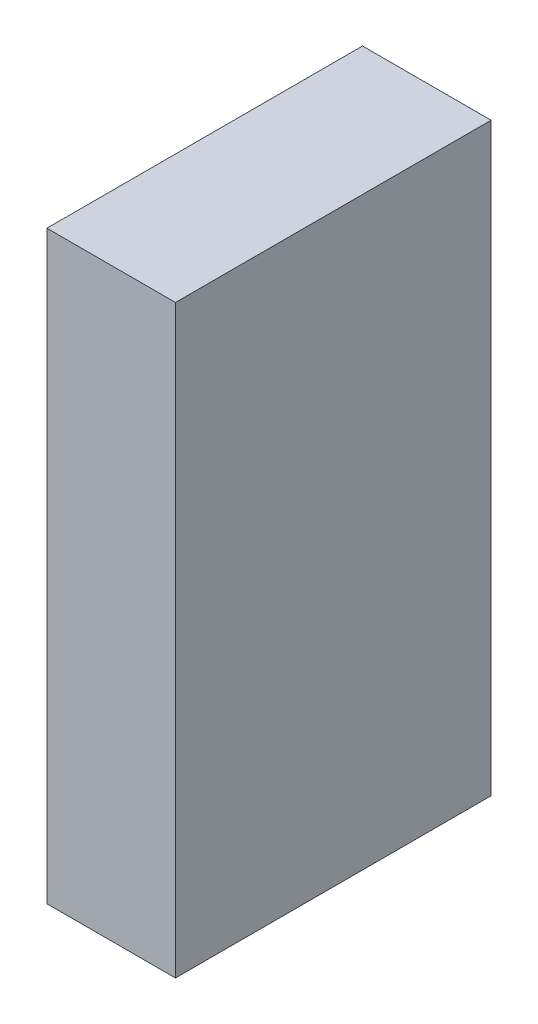
SolidWorks part; units mm, degrees
ref_plane "前视基准面" through (0, 0, 0) normal (0, 0, 1) x (1, 0, 0)
ref_plane "上视基准面" through (0, 0, 0) normal (0, 1, 0) x (1, 0, 0)
ref_plane "右视基准面" through (0, 0, 0) normal (1, 0, 0) x (0, 0, -1)
sketch "草图1" plane through (0, 0, 0) normal (0, 1, 0) x (1, 0, 0)
  line L1 (-9, -25) -> (9, -25)
  line L2 (-9, -25) -> (-9, 25)
  line L3 (-9, 25) -> (9, 25)
  line L4 (9, -25) -> (9, 25)
  line L5 (-9, -25) -> (9, 25) construction
  line L6 (-9, 25) -> (9, -25) construction
  line L7 (-11, -27) -> (11, -27)
  line L8 (-11, -27) -> (-11, 27)
  line L9 (-11, 27) -> (11, 27)
  line L10 (11, -27) -> (11, 27)
  line L11 (-11, -27) -> (11, 27) construction
  line L12 (-11, 27) -> (11, -27) construction
  point P0 (0, 0)
  point P6 (0, 0)
  dimension "D1" = 18
  dimension "D2" = 50
  dimension "D3" = 2
  dimension "D4" = 2
extrude "凸台-拉伸1" add sketch "草图1" along normal blind 100
sketch "草图2" plane through (0, 100, 0) normal (0, 1, 0) x (1, 0, 0)
  line L4 (11, -27) -> (11, 27)
  line L5 (11, 27) -> (-11, 27)
  line L6 (-11, 27) -> (-11, -27)
  line L7 (-11, -27) -> (11, -27)
  line L8 (11, -27) -> (11, 27)
  line L9 (11, 27) -> (-11, 27)
  line L10 (-11, 27) -> (-11, -27)
  line L11 (-11, -27) -> (11, -27)
  dimension "D1" = 0
extrude "凸台-拉伸2" add sketch "草图2" along normal blind 0.1
sketch "草图3" plane through (-11, 0, 0) normal (-1, 0, 0) x (0, 0, 1)
  line L0 (0, 0) -> (0, 64.0629) construction
  circle A0 centre (0, 64.0629) radius 2
  circle A1 centre (0, 53.0629) radius 2
  dimension "D1" = 4
  dimension "D2" = 4
  dimension "D3" = 11
extrude "凸台-拉伸3" add sketch "草图3" against normal up to surface (22 mm away) up to face at (11, 50.05, 0)
